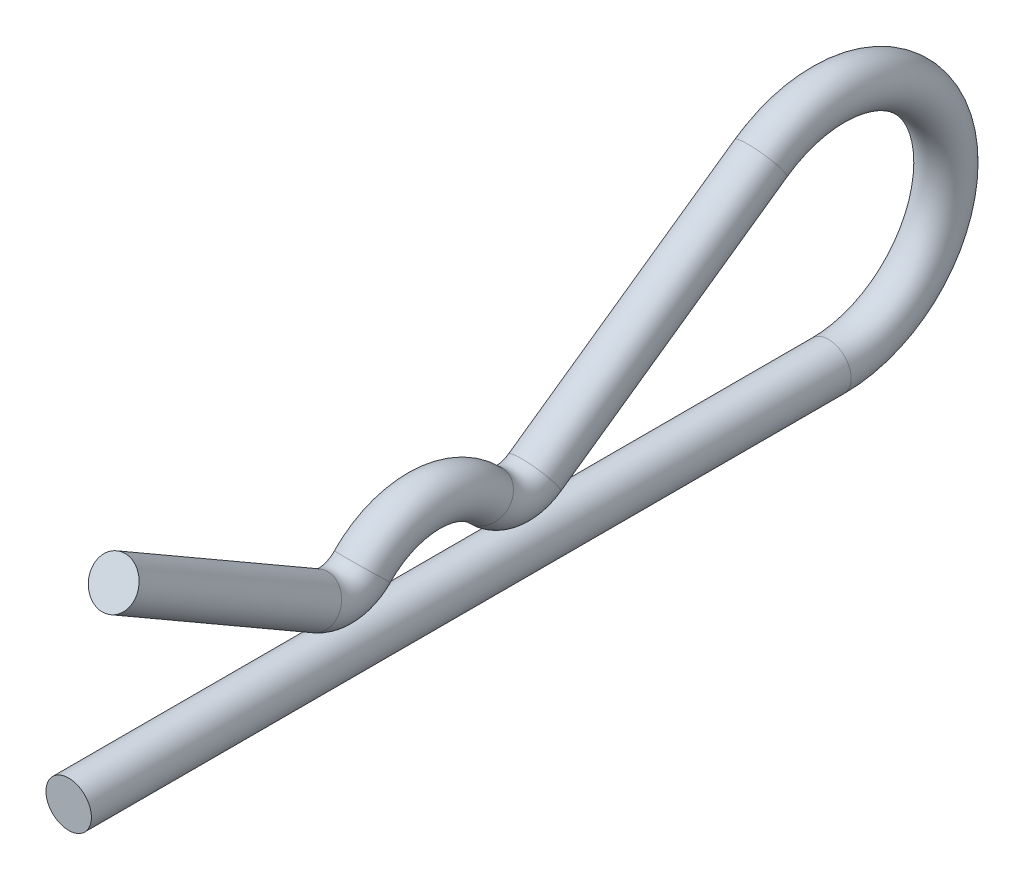
SolidWorks part; units mm, degrees
ref_plane "Front" through (0, 0, 0) normal (0, 0, 1) x (1, 0, 0)
ref_plane "Top" through (0, 0, 0) normal (0, 1, 0) x (1, 0, 0)
ref_plane "Right" through (0, 0, 0) normal (1, 0, 0) x (0, 0, -1)
sketch "Sketch1" plane through (0, 0, 0) normal (1, 0, 0) x (0, 0, -1)
  line L0 (-7.5438, -1.9685) -> (5.1943, -1.9685) construction
  line L1 (-3.0767, -0.5397) -> (-0.0983, -0.5397) construction
  line L2 (7.5438, -1.9685) -> (7.5438, 0) construction
  line L3 (7.5438, 0) -> (7.1628, 0) construction
  line L4 (-7.5438, -1.9685) -> (-7.5438, -1.5875) construction
  line L5 (7.5438, -1.9685) -> (-7.5438, -1.9685) construction
  line L6 (-3.3942, -1.0897) -> (-6.7894, 0.8706) construction
  line L7 (-1.5875, -0.5397) -> (-1.5875, -1.9685) construction
  line L8 (-7.5438, -1.9685) -> (-7.5438, -2.3495) construction
  line L9 (7.5438, -1.9685) -> (7.5438, 1.9685) construction
  line L10 (7.5438, 1.9685) -> (-7.5438, 1.9685) construction
  line L11 (-7.5438, 1.9685) -> (-7.5438, -1.9685) construction
  line L12 (0, 1.9685) -> (0, -1.9685) construction
  line L13 (4.0618, 1.6101) -> (0.267, -1.0591) construction
  line L14 (-7.5438, -1.5875) -> (-2.9873, -1.5875) construction
  line L15 (-2.9873, -1.1684) -> (-2.9873, -1.5875) construction
  circle A0 centre (5.1943, 0) radius 1.5875 construction
  arc A1 (-0.5565, -0.9793) -> (-2.6185, -0.9793) centre (-1.5875, -1.9685) ccw construction
  arc A6 (-2.6185, -0.9793) -> (-3.3942, -1.0897) centre (-3.0767, -0.5397) cw construction
  arc A8 (0.267, -1.0591) -> (-0.5565, -0.9793) centre (-0.0983, -0.5397) cw construction
  arc A9 (5.1943, -1.9685) -> (4.0618, 1.6101) centre (5.1943, 0) ccw construction
  point P2 (0, 0)
  point P25 (-2.9873, -1.1684)
  dimension "D1" = 0.635
  dimension "Eye Diameter" = 3.175
  dimension "D2" = 5.9563
  dimension "D5" = 0.7544
  dimension "D9" = 30
  dimension "D11" = 0.381
  dimension "D3" = 0.381
  dimension "Length" = 15.0876
  dimension "Wire Diameter" = 0.762
  dimension "D4" = 0.4191
ref_plane "Plane1" through (0, 0, 7.5438) normal (0, 0, 1) x (1, 0, 0)
sketch "Sketch3" plane through (0, 0, 7.5438) normal (0, 0, 1) x (1, 0, 0)
  circle A0 centre (0, -1.9685) radius 0.381
sketch "Sketch4" plane through (0, 0, 0) normal (1, 0, 0) x (0, 0, -1)
  line L0 (-3.3942, -1.0897) -> (-6.7894, 0.8706) construction
  line L1 (4.0618, 1.6101) -> (0.267, -1.0591) construction
  line L2 (-7.5438, -1.9685) -> (5.1943, -1.9685) construction
  line L3 (-3.3942, -1.0897) -> (-6.7894, 0.8706)
  line L4 (4.0618, 1.6101) -> (0.267, -1.0591)
  line L5 (-7.5438, -1.9685) -> (5.1943, -1.9685)
  arc A0 (-3.3942, -1.0897) -> (-2.6185, -0.9793) centre (-3.0767, -0.5397) ccw construction
  arc A1 (-0.5565, -0.9793) -> (-2.6185, -0.9793) centre (-1.5875, -1.9685) ccw construction
  arc A2 (-0.5565, -0.9793) -> (0.267, -1.0591) centre (-0.0983, -0.5397) ccw construction
  arc A3 (5.1943, -1.9685) -> (4.0618, 1.6101) centre (5.1943, 0) ccw construction
  arc A4 (-3.3942, -1.0897) -> (-2.6185, -0.9793) centre (-3.0767, -0.5397) ccw
  arc A5 (-0.5565, -0.9793) -> (-2.6185, -0.9793) centre (-1.5875, -1.9685) ccw
  arc A6 (-0.5565, -0.9793) -> (0.267, -1.0591) centre (-0.0983, -0.5397) ccw
  arc A7 (5.1943, -1.9685) -> (4.0618, 1.6101) centre (5.1943, 0) ccw
sweep "Sweep1" add profiles "Sketch3" path "Sketch4"
equation "\"D11@Sketch1\" = \"Wire Diameter@Sketch1\" / 2"
equation "\"D1@Sketch1\" = \"Eye Diameter@Sketch1\" / 5"
equation "\"D3@Sketch1\" = \"D11@Sketch1\""
equation "\"D2@Sketch1\" =  ( \"Length@Sketch1\" - \"Eye Diameter@Sketch1\" )  / 2"
equation "\"D5@Sketch1\" = \"Length@Sketch1\" * .05"
equation "\"D4@Sketch1\" = \"Wire Diameter@Sketch1\" * .55"
